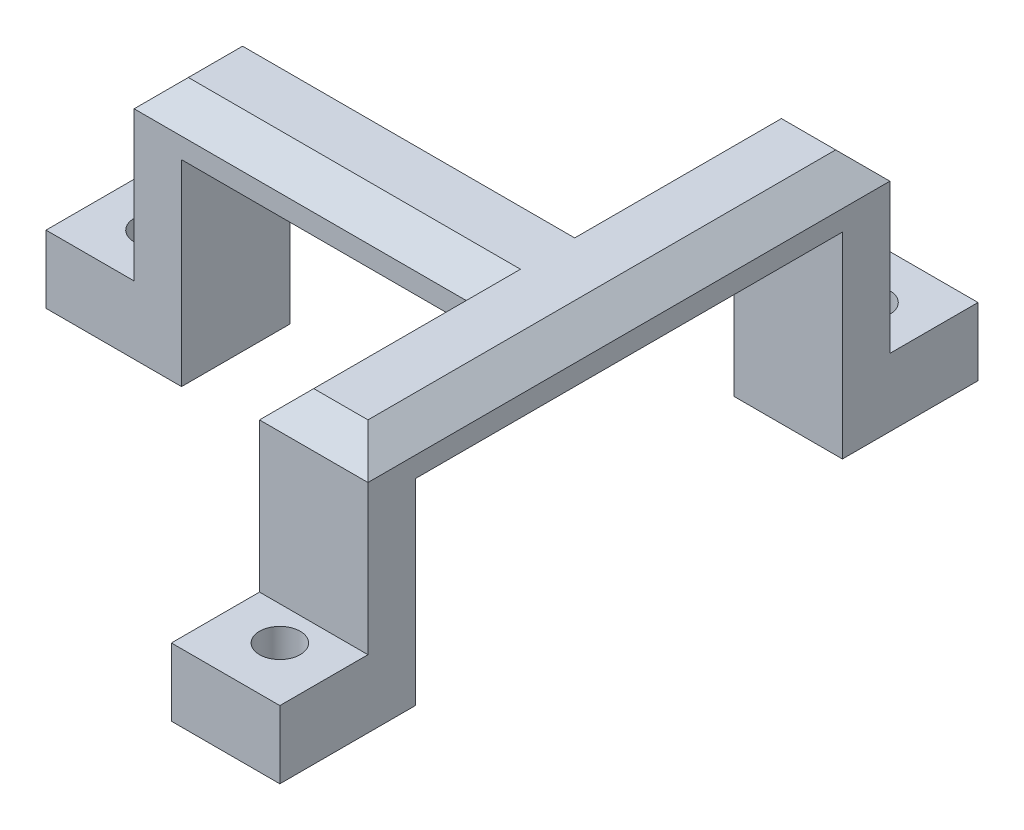
SolidWorks part; units mm, degrees
ref_plane "Ön Düzlem" through (0, 0, 0) normal (0, 0, 1) x (1, 0, 0)
ref_plane "Üst Düzlem" through (0, 0, 0) normal (0, 1, 0) x (1, 0, 0)
ref_plane "Sağ Düzlem" through (0, 0, 0) normal (1, 0, 0) x (0, 0, -1)
sketch "Çizim1" plane through (0, 0, 0) normal (0, 1, 0) x (1, 0, 0)
  line L1 (-35, 4) -> (-25, 4)
  line L2 (-35, 4) -> (-35, -4)
  line L3 (-35, -4) -> (-25, -4)
  line L4 (-25, 4) -> (-25, -4)
  line L5 (-4, 25.75) -> (4, 25.75)
  line L6 (-4, 25.75) -> (-4, 15.75)
  line L7 (-4, 15.75) -> (4, 15.75)
  line L8 (4, 25.75) -> (4, 15.75)
  line L9 (-4, -15.75) -> (4, -15.75)
  line L10 (-4, -15.75) -> (-4, -25.75)
  line L11 (-4, -25.75) -> (4, -25.75)
  line L12 (4, -15.75) -> (4, -25.75)
  circle A0 centre (-31, 0) radius 1.5
  circle A1 centre (0, 21.75) radius 1.5
  circle A2 centre (0, -21.75) radius 1.5
  point P18 (5.7616, 21.75)
  dimension "D2" = 3
  dimension "D5" = 4
  dimension "D10" = 3
  dimension "D11" = 6
  dimension "D13" = 4
  dimension "D14" = 4
  dimension "D17" = 3
  dimension "D18" = 6
  dimension "D1" = 10
  dimension "D3" = 6
  dimension "D4" = 8
  dimension "D6" = 25
  dimension "D7" = 31.5
  dimension "D8" = 15.75
  dimension "D9" = 10
  dimension "D12" = 8
  dimension "D15" = 8
  dimension "D16" = 10
extrude "Yükseklik-Ekstrüzyon1" add sketch "Çizim1" along normal blind 5
sketch "Çizim2" plane through (0, 5, 0) normal (0, 1, 0) x (1, 0, 0)
  line L0 (-35, -4) -> (-25, -4) construction
  line L1 (-25, 4) -> (-28.5, 4)
  line L2 (-25, 4) -> (-25, -4)
  line L3 (-25, -4) -> (-28.5, -4)
  line L4 (-28.5, 4) -> (-28.5, -4)
  line L5 (-4, 25.75) -> (-4, 15.75) construction
  line L6 (-4, 19.25) -> (4, 19.25)
  line L7 (-4, 19.25) -> (-4, 15.75)
  line L8 (-4, 15.75) -> (4, 15.75)
  line L9 (4, 19.25) -> (4, 15.75)
  line L10 (-4, -15.75) -> (-4, -25.75) construction
  line L11 (-4, -19.25) -> (4, -19.25)
  line L12 (-4, -19.25) -> (-4, -15.75)
  line L13 (-4, -15.75) -> (4, -15.75)
  line L14 (4, -19.25) -> (4, -15.75)
  dimension "D1" = 3.5
  dimension "D2" = 3.5
  dimension "D3" = 3.5
extrude "Yükseklik-Ekstrüzyon2" add sketch "Çizim2" along normal blind 13
sketch "Çizim3" plane through (-25, 0, 0) normal (1, 0, 0) x (0, 0, -1)
  line L0 (-4, 18) -> (-4, 0) construction
  line L1 (4, 18) -> (-4, 18)
  line L2 (4, 18) -> (4, 14.5)
  line L3 (4, 14.5) -> (-4, 14.5)
  line L4 (-4, 18) -> (-4, 14.5)
  dimension "D1" = 3.5
extrude "Yükseklik-Ekstrüzyon3" add sketch "Çizim3" along normal up to surface (29 mm away) up to face at (4, 7.6667, 20.25)
sketch "Çizim4" plane through (0, 0, -15.75) normal (0, 0, 1) x (1, 0, 0)
  line L0 (4, 14.5) -> (-25, 14.5) construction
  line L1 (4, 18) -> (-4, 18)
  line L2 (4, 18) -> (4, 14.5)
  line L3 (4, 14.5) -> (-4, 14.5)
  line L4 (-4, 18) -> (-4, 14.5)
  line L5 (-4, 18) -> (-4, 5) construction
  point P9 (-4, 14.5)
extrude "Yükseklik-Ekstrüzyon4" add sketch "Çizim4" along normal up to surface (11.75 mm away) up to face at (-21.125, 9.375, -4)
sketch "Çizim5" plane through (0, 0, 15.75) normal (0, 0, -1) x (-1, 0, 0)
  line L1 (-4, 18) -> (4, 18)
  line L2 (-4, 18) -> (-4, 14.5)
  line L3 (-4, 14.5) -> (4, 14.5)
  line L4 (4, 18) -> (4, 14.5)
extrude "Yükseklik-Ekstrüzyon5" add sketch "Çizim5" along normal up to surface (11.75 mm away) up to face at (-21.125, 9.375, 4)
chamfer "Pah1" distance 2 angle 45 8 edges at (-16.25, 18, 4) (-28.5, 18, 0) (-16.25, 18, -4) (-4, 18, -11.625) (0, 18, -19.25) (4, 18, 0) (0, 18, 19.25) (-4, 18, 11.625)
